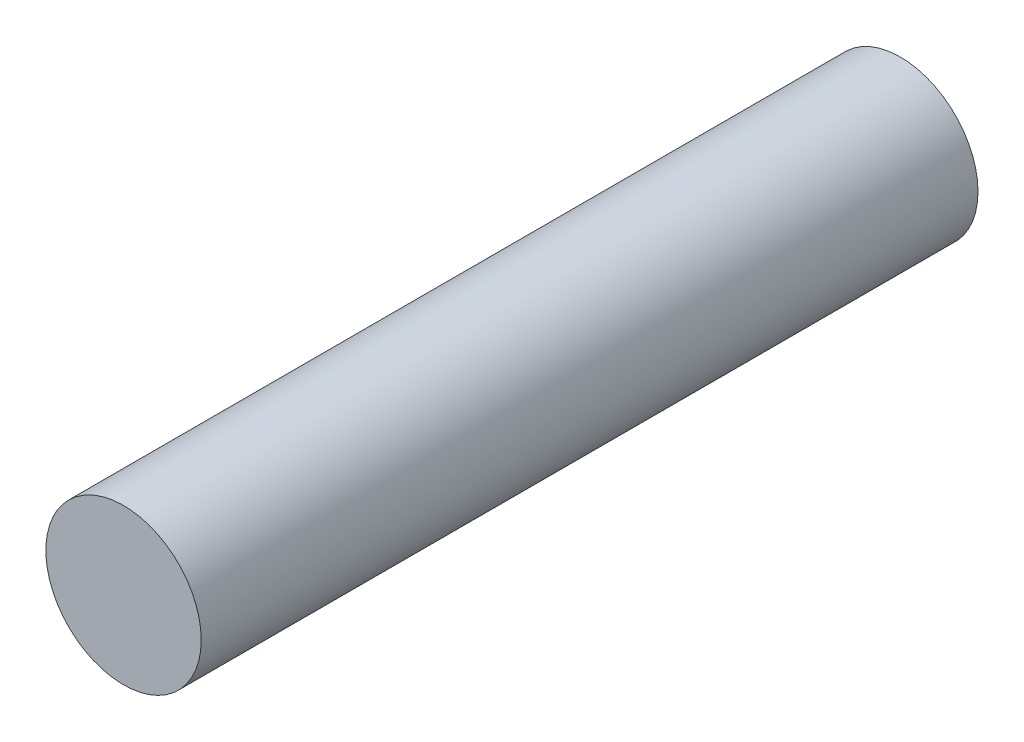
SolidWorks part; units mm, degrees
ref_plane "Front Plane" through (0, 0, 0) normal (0, 0, 1) x (1, 0, 0)
ref_plane "Top Plane" through (0, 0, 0) normal (0, 1, 0) x (1, 0, 0)
ref_plane "Right Plane" through (0, 0, 0) normal (1, 0, 0) x (0, 0, -1)
sketch "Sketch1" plane through (0, 0, 0) normal (1, 0, 0) x (0, 0, -1)
  line L0 (-4.445, 0) -> (4.445, 0) construction
  line L1 (0, -0.889) -> (0, 0.889) construction
  line L2 (-4.445, -0.889) -> (-4.445, 0.889) construction
  line L3 (4.445, -0.889) -> (4.445, 0.889) construction
  point P0 (-2.4536, 0)
  point P4 (0, 0)
  point P8 (0, 0)
  point P11 (-4.445, 0)
  point P14 (4.445, 0)
  point P15 (2.4536, 0)
  point P17 (4.445, 0.889)
  point P18 (4.445, -0.889)
  point P19 (0, 0.889)
  point P20 (0, -0.889)
  point P21 (-4.445, 0.889)
  point P22 (-4.445, -0.889)
  dimension "Width" = 1.778
  dimension "Length" = 8.89
  dimension "D2" = 1.9914
  dimension "D3" = 1.9914
sketch "Sketch2" plane through (0, 0, 0) normal (0, 0, 1) x (1, 0, 0)
  line L0 (-0.889, 0) -> (0.889, 0) construction
  point P4 (0, 0)
  point P5 (0.889, 0)
  point P7 (-0.889, 0)
  dimension "Width" = 1.778
sketch "Sketch3" plane through (0, 0, 0) normal (0, 0, 1) x (1, 0, 0)
  circle A0 centre (0, 0) radius 0.889
extrude "Boss-Extrude1" add sketch "Sketch3" along normal up to vertex (4.445 mm away) and the other way up to vertex (4.445 mm away) up to point (0, 0, 4.445) other way up to point (0, 0, -4.445)
equation "\"Length@Sketch1\"=\"Width@Sketch1\"*5"
equation "\"Width@Sketch2\" = \"Width@Sketch1\""
equation "\"D2@Sketch1\"=\"Width@Sketch1\"*1.12"
equation "\"D3@Sketch1\"=\"Width@Sketch1\"*1.12"
